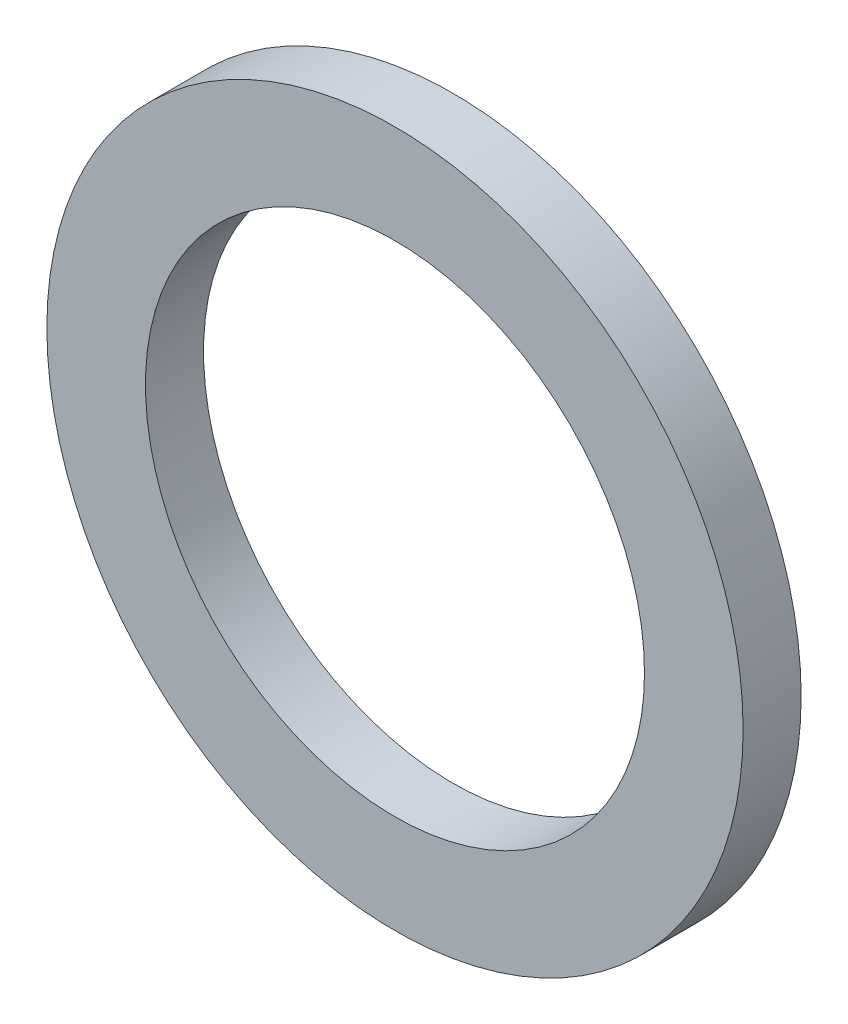
SolidWorks part; units mm, degrees
material "钢"
ref_plane "前视基准面" through (0, 0, 0) normal (0, 0, 1) x (1, 0, 0)
ref_plane "上视基准面" through (0, 0, 0) normal (0, 1, 0) x (1, 0, 0)
ref_plane "右视基准面" through (0, 0, 0) normal (1, 0, 0) x (0, 0, -1)
sketch "草图1" plane through (0, 0, 0) normal (0, 0, 1) x (1, 0, 0)
  circle A0 centre (0, 0) radius 3
  circle A1 centre (0, 0) radius 2.15
  dimension "d2" = 6
  dimension "d1" = 4.3
extrude "拉伸1" add sketch "草图1" along normal blind 0.5
